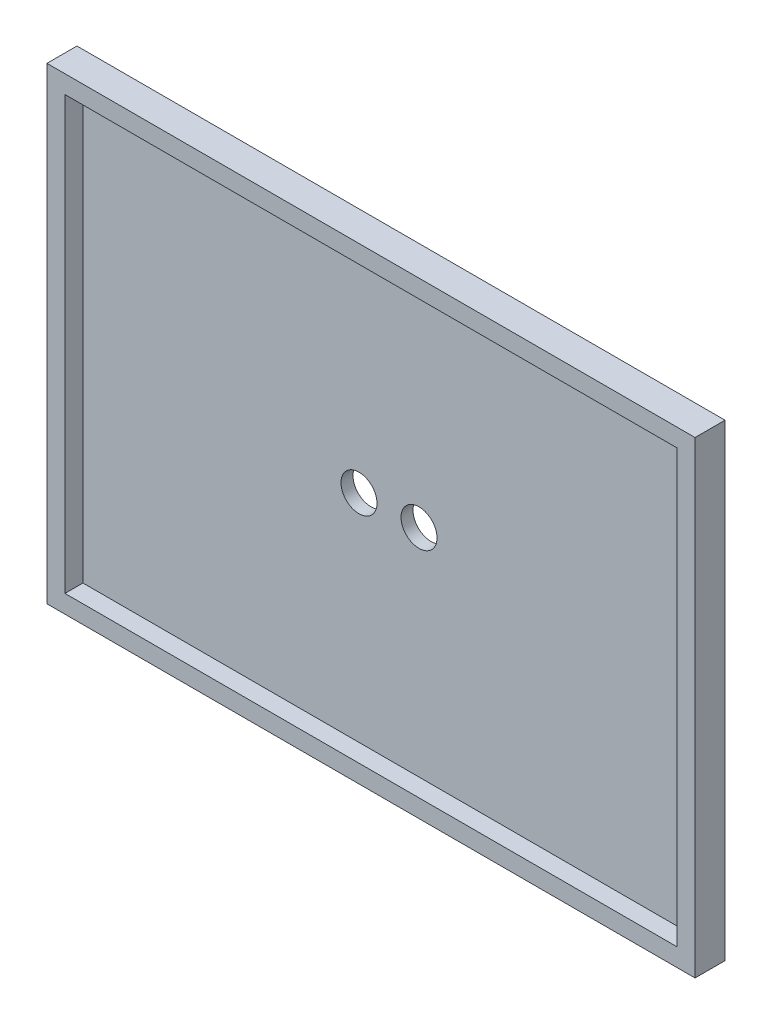
SolidWorks part; units mm, degrees
ref_plane "Ebene vorne" through (0, 0, 0) normal (0, 0, 1) x (1, 0, 0)
ref_plane "Ebene oben" through (0, 0, 0) normal (0, 1, 0) x (1, 0, 0)
ref_plane "Ebene rechts" through (0, 0, 0) normal (1, 0, 0) x (0, 0, -1)
sketch "Skizze1" plane through (0, 0, 0) normal (0, 0, 1) x (1, 0, 0)
  line L1 (-88.9205, 48.0245) -> (19.0795, 48.0245)
  line L2 (-88.9205, 48.0245) -> (-88.9205, -29.9755)
  line L3 (-88.9205, -29.9755) -> (19.0795, -29.9755)
  line L4 (19.0795, 48.0245) -> (19.0795, -29.9755)
  dimension "D1" = 108
  dimension "D2" = 78
extrude "Aufsatz-Linear austragen1" add sketch "Skizze1" along normal blind 5
sketch "Skizze2" plane through (0, 0, 5) normal (0, 0, 1) x (1, 0, 0)
  line L0 (19.0795, 48.0245) -> (-88.9205, 48.0245) construction
  line L1 (-85.9205, 45.0245) -> (16.0795, 45.0245)
  line L2 (-85.9205, 45.0245) -> (-85.9205, -26.9755)
  line L3 (-85.9205, -26.9755) -> (16.0795, -26.9755)
  line L4 (16.0795, 45.0245) -> (16.0795, -26.9755)
  line L5 (-88.9205, 48.0245) -> (-88.9205, -29.9755) construction
  dimension "D1" = 102
  dimension "D2" = 72
  dimension "D3" = 3
  dimension "D4" = 3
extrude "Schnitt-Linear austragen1" cut sketch "Skizze2" against normal blind 3
sketch "Skizze3" plane through (0, 0, 2) normal (0, 0, 1) x (1, 0, 0)
  line L0 (16.0795, 45.0245) -> (-85.9205, 45.0245) construction
  line L1 (-85.9205, 45.0245) -> (-85.9205, -26.9755) construction
  line L2 (16.0795, -26.9755) -> (16.0795, 45.0245) construction
  circle A0 centre (-39.9205, 9.0245) radius 3
  circle A1 centre (-29.9205, 9.0245) radius 3
  dimension "D5" = 6
  dimension "D6" = 6
  dimension "D1" = 36
  dimension "D2" = 36
  dimension "D3" = 46
  dimension "D4" = 46
extrude "Schnitt-Linear austragen2" cut sketch "Skizze3" against normal blind 3
sketch "Skizze5" plane through (-88.9205, 0, 0) normal (-1, 0, 0) x (0, 0, 1)
  line L0 (5, 37.2587) -> (0, 32.2587) construction
  line L1 (5, 48.0245) -> (5, -29.9755) construction
  line L2 (0, 48.0245) -> (0, -29.9755) construction
sketch "Skizze4" plane through (0, 0, 0) normal (0, 0, -1) x (-1, 0, 0)
  line L0 (-19.0795, -29.9755) -> (-19.0795, 48.0245) construction
  line L1 (-19.0795, 48.0245) -> (88.9205, 48.0245) construction
  circle A0 centre (34.9205, 28.0245) radius 10
  circle A1 centre (34.9205, 28.0245) radius 3
  dimension "D3" = 6
  dimension "D4" = 20
  dimension "D1" = 54
  dimension "D2" = 20
extrude "Aufsatz-Linear austragen2" add sketch "Skizze4" along direction (0, -0.7071, -0.7071) on the side of the normal blind 25
